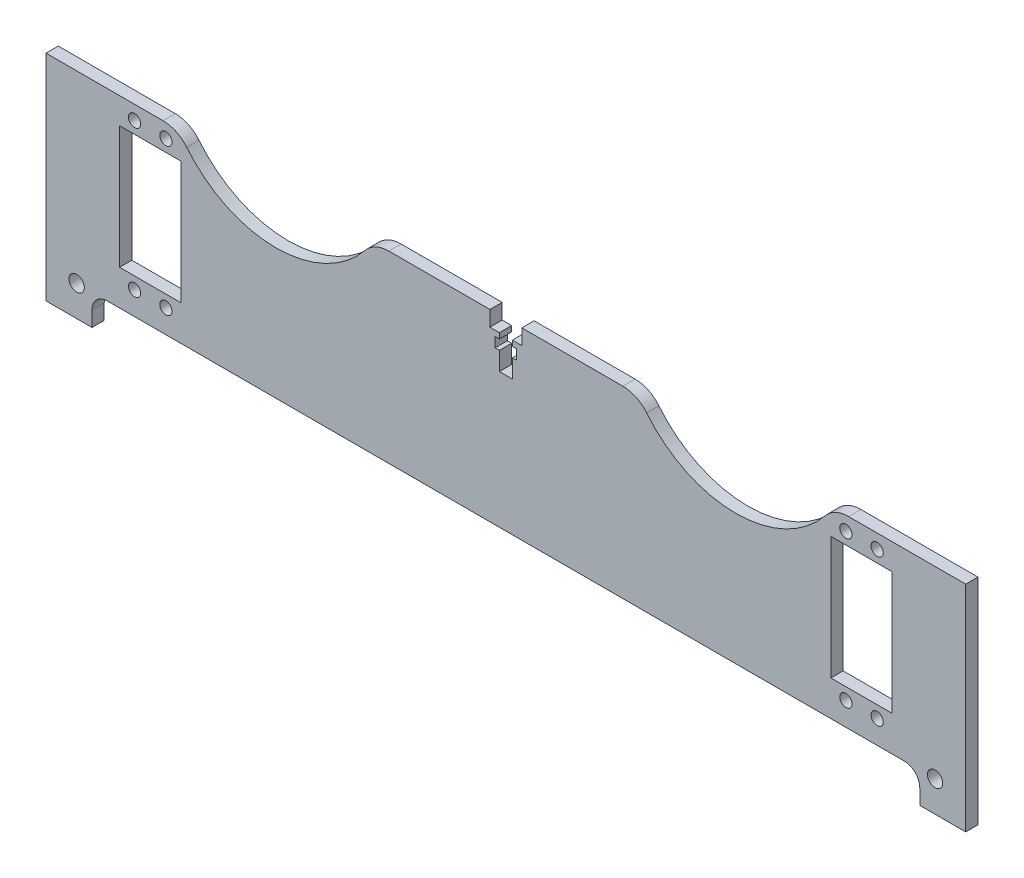
SolidWorks part; units mm, degrees
ref_plane "Plan de face" through (0, 0, 0) normal (0, 0, 1) x (1, 0, 0)
ref_plane "Plan de dessus" through (0, 0, 0) normal (0, 1, 0) x (1, 0, 0)
ref_plane "Plan de droite" through (0, 0, 0) normal (1, 0, 0) x (0, 0, -1)
sketch "Esquisse1" plane through (0, 0, 0) normal (0, 0, 1) x (1, 0, 0)
  line L1 (150, -35) -> (-150, -35)
  line L2 (150, -35) -> (150, 35)
  line L3 (150, 35) -> (-150, 35)
  line L4 (-150, -35) -> (-150, 35)
  line L5 (150, -35) -> (-150, 35) construction
  line L6 (150, 35) -> (-150, -35) construction
  point P0 (0, 0)
  dimension "D1" = 300
  dimension "D2" = 70
extrude "Boss.-Extru.1" add sketch "Esquisse1" along normal blind 4
sketch "Esquisse2" plane through (0, 0, 4) normal (0, 0, 1) x (1, 0, 0)
  line L0 (-150, -35) -> (150, -35) construction
  line L1 (-135, -25) -> (0, -25)
  line L2 (-135, -25) -> (-135, -35)
  line L3 (-135, -35) -> (0, -35)
  line L5 (0, 0) -> (0, -35) construction
  line L7 (135, -35) -> (0, -35)
  line L8 (135, -25) -> (135, -35)
  line L9 (135, -25) -> (0, -25)
  line L10 (-150, 35) -> (-150, -35) construction
  line L11 (150, -35) -> (150, 35) construction
  line L12 (150, 35) -> (-150, 35) construction
  circle A0 centre (140, -25) radius 2.5
  circle A1 centre (-140, -25) radius 2.5
  dimension "D4" = 10
  dimension "D5" = 5
  dimension "D1" = 15
  dimension "D3" = 10
  dimension "D6" = 60
extrude "Enlèv. mat.-Extru.1" cut sketch "Esquisse2" against normal through all
sketch "Esquisse3" plane through (0, 0, 0) normal (0, 0, -1) x (-1, 0, 0)
  line L0 (0, 0) -> (0, 35) construction
  line L1 (-150, 35) -> (150, 35) construction
  circle A0 centre (75, 55) radius 37.5
  circle A1 centre (-75, 55) radius 37.5
  dimension "D1" = 75
extrude "Enlèv. mat.-Extru.2" cut sketch "Esquisse3" against normal through all
fillet "Congé1" radius 10 4 edges at (106.7214, 35, 2) (43.2786, 35, 2) (-43.2786, 35, 2) (-106.7214, 35, 2)
sketch "Esquisse4" plane through (0, 0, 4) normal (0, 0, 1) x (1, 0, 0)
  line L0 (-126, -9.25) -> (-126, 22.25) construction
  line L1 (-126, 26.5) -> (-106, 26.5)
  line L2 (-126, 26.5) -> (-126, -13.5)
  line L3 (-126, -13.5) -> (-106, -13.5)
  line L4 (-106, 26.5) -> (-106, -13.5)
  line L5 (106, 26.5) -> (106, -13.5)
  line L6 (-110.25, -13.5) -> (-121.75, -13.5) construction
  line L7 (-106, 22.25) -> (-106, -9.25) construction
  line L8 (-121.75, 26.5) -> (-110.25, 26.5) construction
  line L9 (0, 0) -> (0, 35) construction
  line L10 (38.1727, 35) -> (-38.1727, 35) construction
  line L11 (126, -13.5) -> (106, -13.5)
  line L12 (126, 26.5) -> (126, -13.5)
  line L13 (126, 26.5) -> (106, 26.5)
  circle A0 centre (-110.9, 30.4) radius 2
  circle A1 centre (-121.1, 30.4) radius 2
  circle A2 centre (-110.9, -17.4) radius 2
  circle A3 centre (-121.1, -17.4) radius 2
  circle A4 centre (121.1, -17.4) radius 2
  circle A5 centre (110.9, -17.4) radius 2
  circle A6 centre (121.1, 30.4) radius 2
  circle A7 centre (110.9, 30.4) radius 2
  dimension "D5" = 4
  dimension "D1" = 0
  dimension "D2" = 0
  dimension "D3" = 0
  dimension "D4" = 0
extrude "Enlèv. mat.-Extru.3" cut sketch "Esquisse4" against normal through all
fillet "Congé2" radius 5 2 edges at (135, -25, 2) (-135, -25, 2)
sketch "Esquisse5" plane through (0, 35, 0) normal (0, 1, 0) x (1, 0, 0)
  line L0 (-5, -4) -> (5, -4) construction
  line L1 (-5, -4) -> (-5, 0) construction
  line L2 (5, -4) -> (5, 0) construction
  line L3 (-5, 0) -> (5, 0) construction
  line L4 (38.1727, -4) -> (-38.1727, -4) construction
  line L5 (-5, -2) -> (-5, -4) construction
  line L6 (5, -4) -> (5, -2) construction
  line L8 (38.1727, 0) -> (-38.1727, 0) construction
  line L9 (-5.2, -4.2) -> (5.2, -4.2)
  line L10 (5.2, -4.2) -> (5.2, 0.2)
  line L11 (-5.2, 0.2) -> (5.2, 0.2)
  line L12 (-5.2, -4.2) -> (-5.2, 0.2)
  dimension "D1" = 0.2
extrude "Enlèv. mat.-Extru.4" cut sketch "Esquisse5" against normal blind 5
sketch "Esquisse6" plane through (0, 0, 0) normal (0, 0, -1) x (-1, 0, 0)
  line L0 (0, 30) -> (0, 19) construction
  line L1 (5.2, 30) -> (-5.2, 30) construction
  line L2 (-2.1, 30) -> (2.1, 30)
  line L3 (2.1, 30) -> (2.1, 28.2)
  line L4 (2.1, 28.2) -> (3.5, 28.2)
  line L5 (3.5, 28.2) -> (3.5, 25)
  line L6 (3.5, 25) -> (2.1, 25)
  line L7 (2.1, 25) -> (2.1, 19)
  line L8 (2.1, 19) -> (-2.1, 19)
  line L9 (-2.1, 25) -> (-2.1, 19)
  line L10 (-3.5, 25) -> (-2.1, 25)
  line L11 (-3.5, 28.2) -> (-3.5, 25)
  line L12 (-2.1, 28.2) -> (-3.5, 28.2)
  line L13 (-2.1, 30) -> (-2.1, 28.2)
  dimension "D1" = 4.2
  dimension "D2" = 7
  dimension "D3" = 5
  dimension "D4" = 11
  dimension "D5" = 3.2
extrude "Enlèv. mat.-Extru.5" cut sketch "Esquisse6" against normal through all
